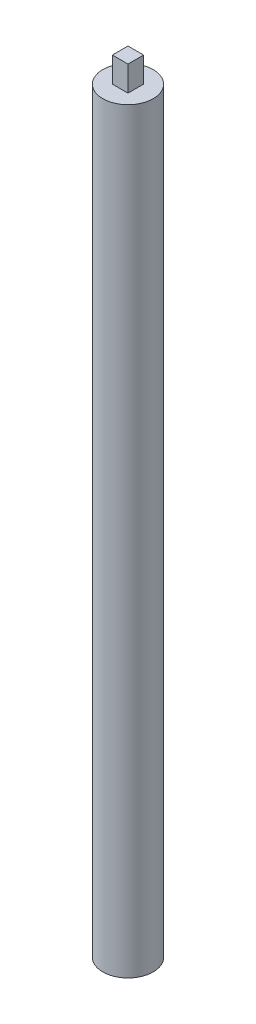
SolidWorks part; units mm, degrees
ref_plane "Front Plane" through (0, 0, 0) normal (0, 0, 1) x (1, 0, 0)
ref_plane "Top Plane" through (0, 0, 0) normal (0, 1, 0) x (1, 0, 0)
ref_plane "Right Plane" through (0, 0, 0) normal (1, 0, 0) x (0, 0, -1)
sketch "Sketch1" plane through (0, 0, 0) normal (0, 1, 0) x (1, 0, 0)
  circle A0 centre (0, 0) radius 12.7
  dimension "D1" = 25.4
extrude "Boss-Extrude1" add sketch "Sketch1" along normal blind 381
sketch "Sketch2" plane through (0, 381, 0) normal (0, 1, 0) x (1, 0, 0)
  line L1 (3.9368, -3.935) -> (-3.9368, -3.935)
  line L2 (3.9368, -3.935) -> (3.9368, 3.935)
  line L3 (3.9368, 3.935) -> (-3.9368, 3.935)
  line L4 (-3.9368, -3.935) -> (-3.9368, 3.935)
  line L5 (3.9368, -3.935) -> (-3.9368, 3.935) construction
  line L6 (3.9368, 3.935) -> (-3.9368, -3.935) construction
  point P0 (0, 0)
extrude "Boss-Extrude2" add sketch "Sketch2" along normal blind 12.7
